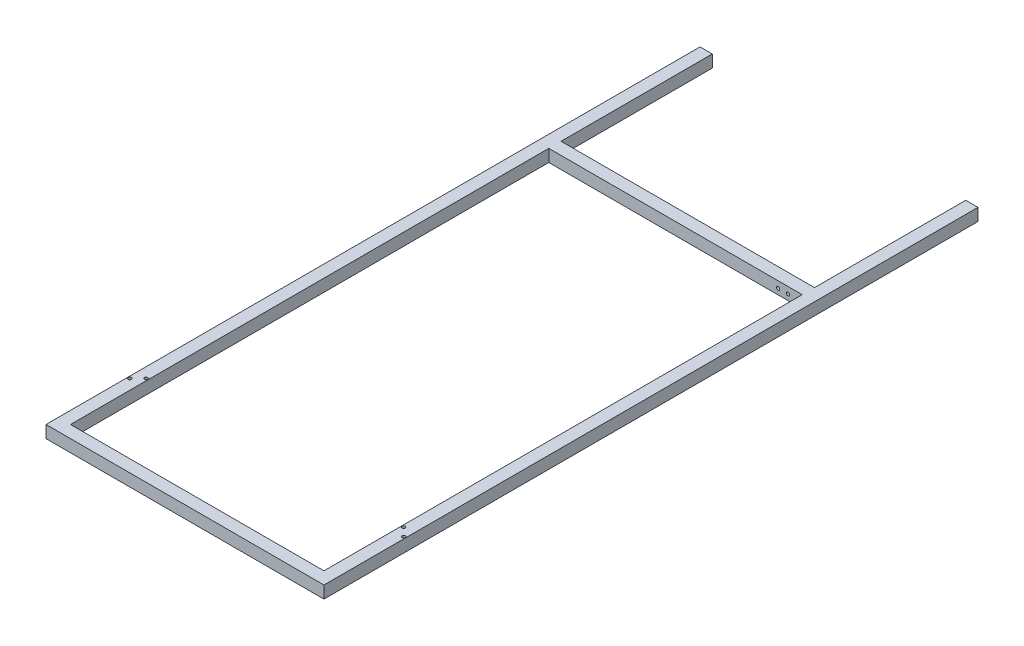
SolidWorks part; units mm, degrees
ref_plane "前视基准面" through (0, 0, 0) normal (0, 0, 1) x (1, 0, 0)
ref_plane "上视基准面" through (0, 0, 0) normal (0, 1, 0) x (1, 0, 0)
ref_plane "右视基准面" through (0, 0, 0) normal (1, 0, 0) x (0, 0, -1)
sketch "草图2" plane through (0, 0, 0) normal (0, 1, 0) x (1, 0, 0)
  line L0 (-167.3575, 0) -> (172.6425, 0)
  line L1 (172.6425, 0) -> (172.6425, -800)
  line L2 (-167.3575, 0) -> (-167.3575, -800)
  line L3 (-167.3575, -800) -> (172.6425, -800)
  dimension "D1" = 340
  dimension "D2" = 800
extrude "凸台-拉伸1" add sketch "草图2" along normal blind 15
sketch "草图3" plane through (0, 15, 0) normal (0, 1, 0) x (1, 0, 0)
  line L0 (-152.3575, 0) -> (-152.3575, -785)
  line L1 (172.6425, 0) -> (-167.3575, 0) construction
  line L2 (-152.3575, -785) -> (157.6425, -785)
  line L3 (157.6425, -785) -> (157.6425, 0)
  line L4 (157.6425, 0) -> (-152.3575, 0)
  line L5 (-167.3575, 0) -> (-167.3575, -800) construction
  line L6 (172.6425, -800) -> (172.6425, 0) construction
  line L7 (-167.3575, -800) -> (172.6425, -800) construction
  dimension "D1" = 15
  dimension "D2" = 15
  dimension "D3" = 15
extrude "切除-拉伸1" cut sketch "草图3" against normal blind 15
ref_plane "基准面1" through (172.6425, 0, 0) normal (0, 0, -1) x (-1, 0, 0)
sketch "草图8" plane through (0, 15, 0) normal (0, 1, 0) x (1, 0, 0)
  line L0 (-152.3575, -185) -> (157.6425, -185)
  line L1 (-152.3575, 0) -> (-152.3575, -785) construction
  line L2 (157.6425, -785) -> (157.6425, 0) construction
  line L3 (157.6425, -185) -> (157.6425, -200)
  line L4 (157.6425, -200) -> (-152.3575, -200)
  line L5 (-152.3575, -200) -> (-152.3575, -185)
  line L6 (-152.3575, -785) -> (157.6425, -785) construction
  dimension "D1" = 600
  dimension "D2" = 15
extrude "凸台-拉伸3" add sketch "草图8" against normal blind 15
sketch "草图10" plane through (0, 0, 185) normal (0, 0, -1) x (-1, 0, 0)
  line L0 (-157.6425, 0) -> (-157.6425, 15) construction
  line L1 (-157.6425, 0) -> (152.3575, 0) construction
  circle A0 centre (-152.1425, 7) radius 2
  circle A1 centre (-140.1425, 7) radius 2
  circle A2 centre (-128.1425, 7) radius 2
  point P8 (-157.6425, 7.5)
  dimension "D4" = 4
  dimension "D5" = 7
  dimension "D1" = 5.5
  dimension "D2" = 12
  dimension "D3" = 12
extrude "切除-拉伸5" cut sketch "草图10" against normal up to next
sketch "草图11" plane through (0, 15, 0) normal (0, 1, 0) x (1, 0, 0)
  line L0 (172.6425, -800) -> (172.6425, 0) construction
  line L1 (157.6425, -785) -> (157.6425, -200) construction
  line L2 (2.6425, -785) -> (2.6425, -553.4101) construction
  line L3 (-152.3575, -785) -> (157.6425, -785) construction
  line L4 (-167.3575, -800) -> (172.6425, -800) construction
  circle A0 centre (160.1425, -690) radius 2
  circle A1 centre (170.1425, -700) radius 2
  circle A2 centre (-154.8575, -690) radius 2
  circle A3 centre (-164.8575, -700) radius 2
  dimension "D1" = 4
  dimension "D2" = 4
  dimension "D3" = 2.5
  dimension "D4" = 2.5
  dimension "D5" = 10
  dimension "D6" = 100
extrude "切除-拉伸6" cut sketch "草图11" against normal through all
